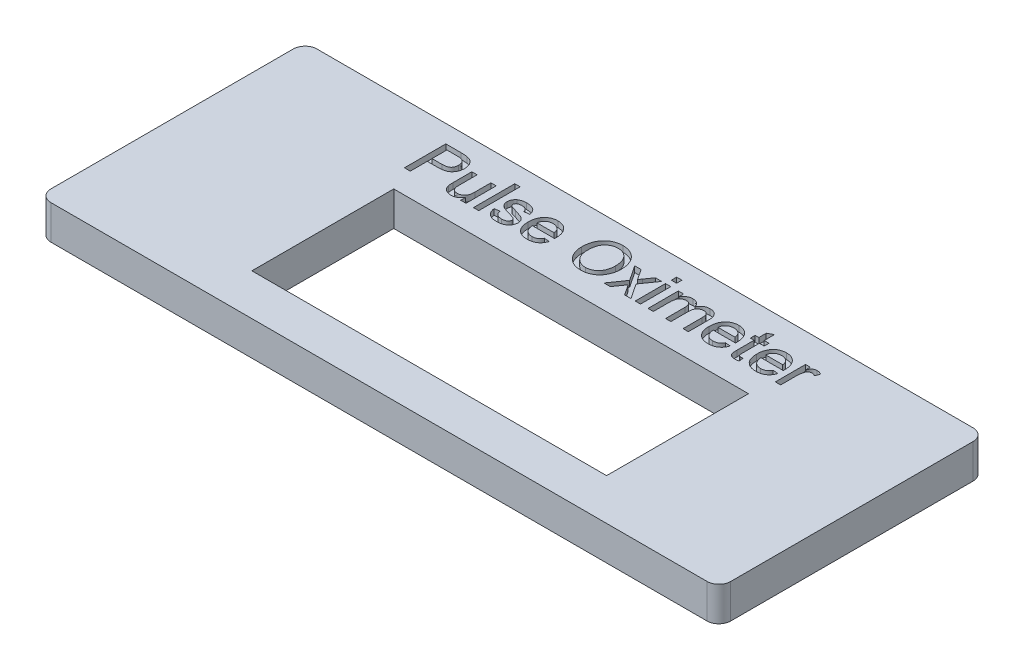
SolidWorks part; units mm, degrees
material "ABS"
ref_plane "Front Plane" through (0, 0, 0) normal (0, 0, 1) x (1, 0, 0)
ref_plane "Top Plane" through (0, 0, 0) normal (0, 1, 0) x (1, 0, 0)
ref_plane "Right Plane" through (0, 0, 0) normal (1, 0, 0) x (0, 0, -1)
sketch "Sketch1" plane through (0, 0, 0) normal (0, 1, 0) x (1, 0, 0)
  line L1 (1, 0) -> (56.5, 0)
  line L2 (0, 1) -> (0, 21.5)
  line L3 (1, 22.5) -> (56.5, 22.5)
  line L4 (57.5, 1) -> (57.5, 21.5)
  arc A0 (56.5, 22.5) -> (57.5, 21.5) centre (56.5, 21.5) cw
  arc A1 (57.5, 1) -> (56.5, 0) centre (56.5, 1) cw
  arc A2 (1, 0) -> (0, 1) centre (1, 1) cw
  arc A3 (0, 21.5) -> (1, 22.5) centre (1, 21.5) cw
  point P11 (0, 0)
  dimension "D1" = 1
extrude "Boss-Extrude1" add sketch "Sketch1" along normal blind 2.9
ref_plane "Plane1" through (0, 3, 0) normal (0, 1, 0) x (1, 0, 0)
sketch "Sketch2" plane through (0, 3, 0) normal (0, 1, 0) x (1, 0, 0)
  line L0 (0, 0) -> (0, 3.5)
  line L1 (0, 21.5) -> (0, 1) construction
  line L2 (0, 3.5) -> (1.5, 3.5)
  line L3 (1.5, 3.5) -> (14.5, 3.5)
  line L4 (14.5, 3.5) -> (44.5, 3.5)
  line L5 (44.5, 3.5) -> (44.5, 15.5)
  line L6 (44.5, 15.5) -> (14.5, 15.5)
  line L7 (14.5, 15.5) -> (14.5, 3.5)
extrude "Cut-Extrude1" cut sketch "Sketch2" against normal blind 10 contours L6 L7 L4 L5
sketch "Sketch3" plane through (0, 2.9, 0) normal (0, 1, 0) x (1, 0, 0)
  text T0 "Pulse Oximeter"
  point P1 (0, 0)
extrude "Cut-Extrude2" cut sketch "Sketch3" against normal blind 0.5
